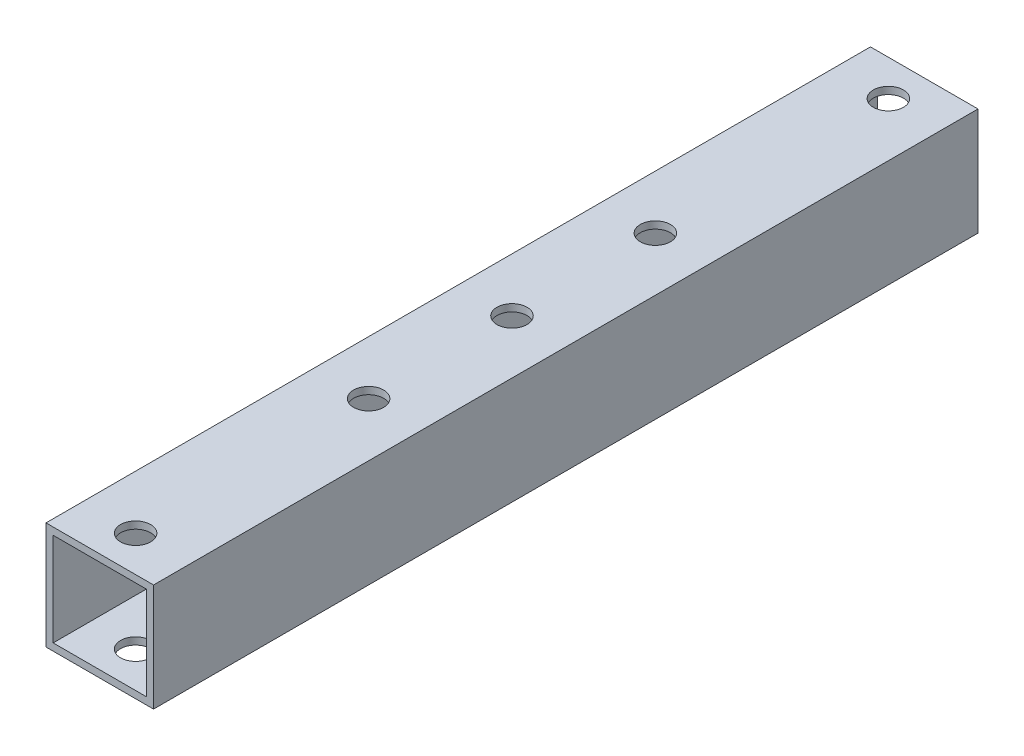
SolidWorks part; units mm, degrees
material "5052-H34"
ref_plane "正面" through (0, 0, 0) normal (0, 0, 1) x (1, 0, 0)
ref_plane "平面" through (0, 0, 0) normal (0, 1, 0) x (1, 0, 0)
ref_plane "右側面" through (0, 0, 0) normal (1, 0, 0) x (0, 0, -1)
sketch "ｽｹｯﾁ1" plane through (0, 0, 0) normal (0, 0, 1) x (1, 0, 0)
  line L1 (7.5, 7.5) -> (-7.5, 7.5)
  line L2 (7.5, 7.5) -> (7.5, -7.5)
  line L3 (7.5, -7.5) -> (-7.5, -7.5)
  line L4 (-7.5, 7.5) -> (-7.5, -7.5)
  line L5 (7.5, 7.5) -> (-7.5, -7.5) construction
  line L6 (7.5, -7.5) -> (-7.5, 7.5) construction
  point P0 (0, 0)
  dimension "D1" = 15
extrude "押し出し-薄板1" add sketch "ｽｹｯﾁ1" along normal blind 115 thin thin type one direction reverse wall 1
sketch "ｽｹｯﾁ2" plane through (0, 7.5, 0) normal (0, 1, 0) x (1, 0, 0)
  line L0 (0, 0) -> (0, -115) construction
  line L1 (7.5, -115) -> (-7.5, -115) construction
  line L2 (0, -57.5) -> (7.5, -57.5)
  line L3 (7.5, -115) -> (7.5, 0) construction
  line L4 (7.5, 0) -> (-7.5, 0) construction
  circle A0 centre (0, -5) radius 2.1
  circle A2 centre (0, -37.5) radius 2.1
  circle A3 centre (0, -57.5) radius 2.1
  circle A4 centre (0, -110) radius 2.1
  circle A6 centre (0, -77.5) radius 2.1
  dimension "D1" = 4.2
  dimension "D2" = 5
  dimension "D4" = 20
  dimension "D5" = 4.2
  dimension "D6" = 4.2
extrude "ｶｯﾄ - 押し出し1" cut sketch "ｽｹｯﾁ2" against normal through all contours L0 A4 | A4 L0 | L0 A6 | A6 L0 | L0 A3 | A3 L0 L2 | L2 L0 A3 | L0 A2 | A2 L0 | L0 A0 | A0 L0
